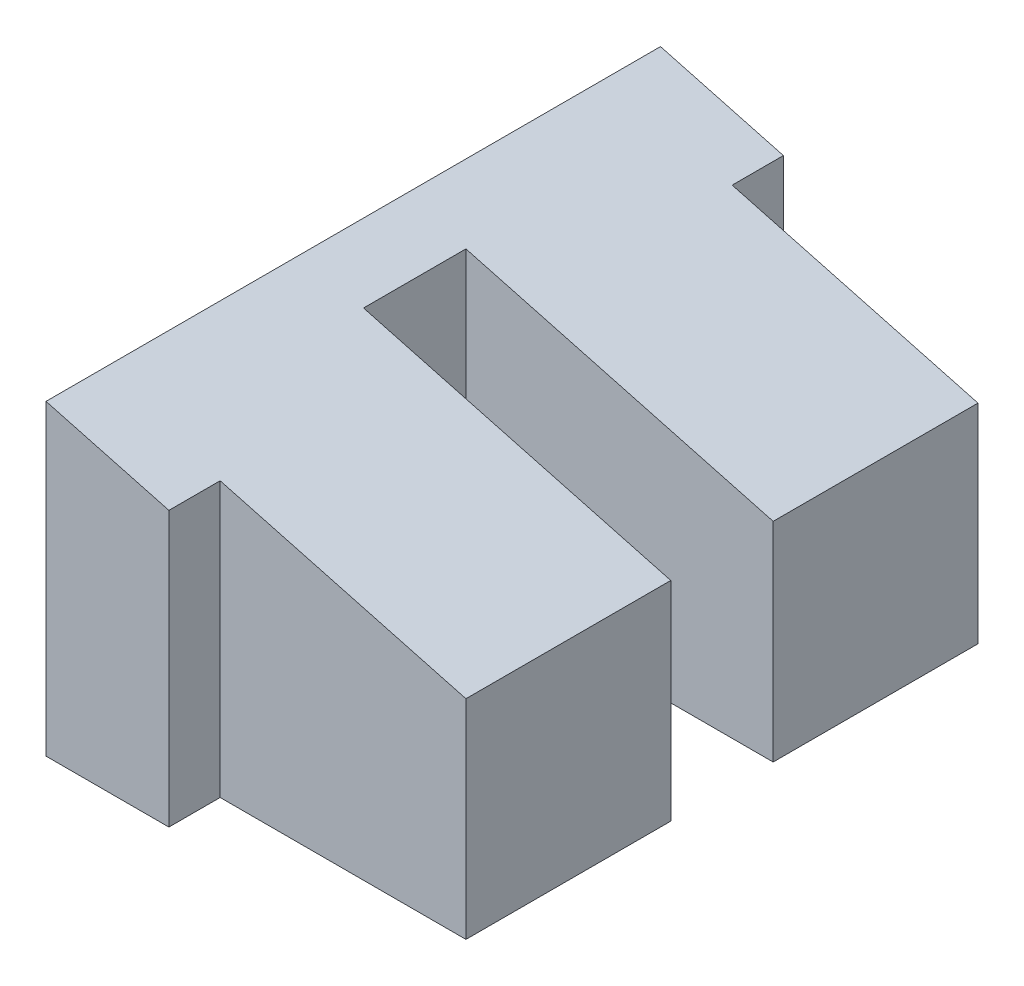
SolidWorks part; units mm, degrees
ref_plane "Alzado" through (0, 0, 0) normal (0, 0, 1) x (1, 0, 0)
ref_plane "Planta" through (0, 0, 0) normal (0, 1, 0) x (1, 0, 0)
ref_plane "Vista lateral" through (0, 0, 0) normal (1, 0, 0) x (0, 0, -1)
sketch "Croquis1" plane through (0, 0, 0) normal (1, 0, 0) x (0, 0, -1)
  line L0 (55, 0) -> (-55, 0) construction
  line L1 (-25, 25) -> (25, 25)
  line L2 (-25, 25) -> (-25, 0)
  line L3 (-25, 0) -> (25, 0)
  line L4 (25, 25) -> (25, 0)
  point P6 (0, 0)
  dimension "D1" = 50
  dimension "D2" = 25
extrude "Saliente-Extruir1" add sketch "Croquis1" along normal blind 10
sketch "Croquis2" plane through (10, 0, 0) normal (1, 0, 0) x (0, 0, -1)
  line L16 (25, 25) -> (-25, 25) construction
  line L21 (-20.83, 25) -> (-4.1633, 25)
  line L22 (-20.83, 25) -> (-20.83, 0)
  line L23 (-20.83, 0) -> (-4.1633, 0)
  line L24 (-4.1633, 25) -> (-4.1633, 0)
  line L25 (-25, 0) -> (25, 0) construction
  line L26 (25, 0) -> (25, 25) construction
  line L27 (4.1683, 25) -> (20.835, 25)
  line L28 (4.1683, 25) -> (4.1683, 0)
  line L29 (4.1683, 0) -> (20.835, 0)
  line L30 (20.835, 25) -> (20.835, 0)
  line L35 (-25, 25) -> (-25, 0) construction
  dimension "D1" = 16.6667
  dimension "D2" = 16.6667
  dimension "D3" = 4.165
  dimension "D4" = 4.17
extrude "Saliente-Extruir2" add sketch "Croquis2" along normal blind 20
sketch "Croquis3" plane through (0, 0, 25) normal (0, 0, 1) x (1, 0, 0)
  line L0 (0, 25) -> (30, 16.9615)
  line L1 (30, 25) -> (30, 0) construction
  line L2 (10, 25) -> (0, 25) construction
  dimension "D1" = 15
extrude "Cortar-Extruir1" cut sketch "Croquis3" against normal through all and the other way through all contours L0
sketch "Croquis5" plane through (0, 0, 0) normal (0, -1, 0) x (1, 0, 0)
  line L1 (10, 4.1633) -> (5, 4.1633)
  line L2 (10, 4.1633) -> (10, -4.1683)
  line L3 (10, -4.1683) -> (5, -4.1683)
  line L4 (5, 4.1633) -> (5, -4.1683)
  line L5 (30, -4.1683) -> (10, -4.1683) construction
  dimension "D1" = 5
extrude "Cortar-Extruir3" cut sketch "Croquis5" against normal through all
